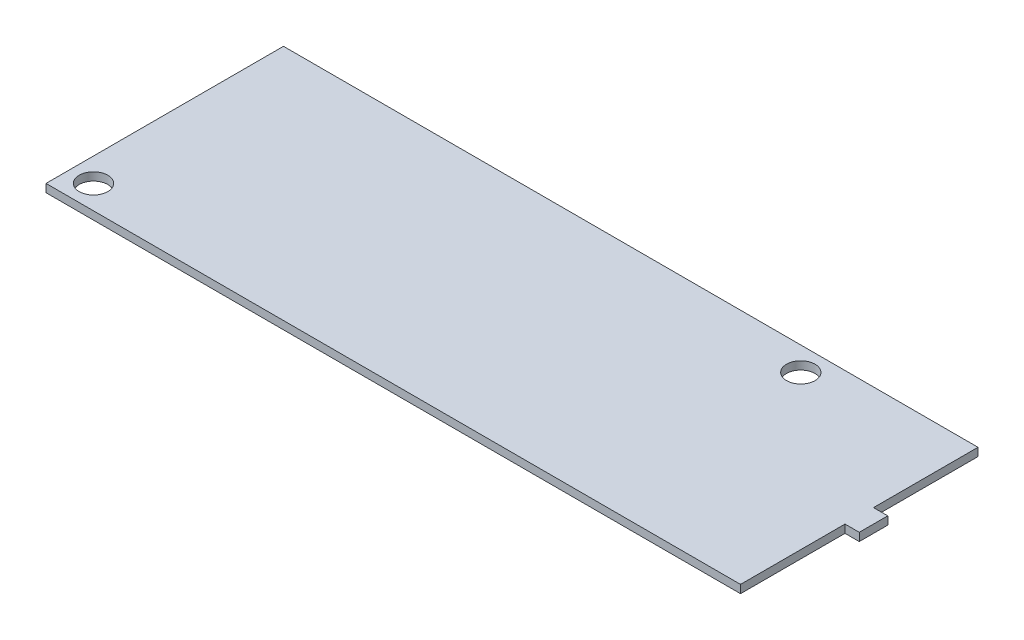
SolidWorks part; units mm, degrees
ref_plane "Alzado" through (0, 0, 0) normal (0, 0, 1) x (1, 0, 0)
ref_plane "Planta" through (0, 0, 0) normal (0, 1, 0) x (1, 0, 0)
ref_plane "Vista lateral" through (0, 0, 0) normal (1, 0, 0) x (0, 0, -1)
sketch "Croquis1" plane through (0, 0, 0) normal (0, 1, 0) x (1, 0, 0)
  line L0 (74.6125, -3) -> (71.6125, -3)
  line L1 (71.6125, 3) -> (74.6125, 3)
  line L2 (-74.6125, 25) -> (71.6125, 25)
  line L3 (71.6125, -25) -> (-74.6125, -25)
  line L4 (-74.6125, -25) -> (-74.6125, 25)
  line L5 (74.6125, -3) -> (74.6125, 3)
  line L6 (71.6125, -25) -> (71.6125, -3)
  line L7 (71.6125, 3) -> (71.6125, 25)
  circle A0 centre (39.306, 20) radius 3
  circle A1 centre (-69.6125, -20) radius 3
extrude "Saliente-Extruir1" add sketch "Croquis1" along normal blind 1.7
